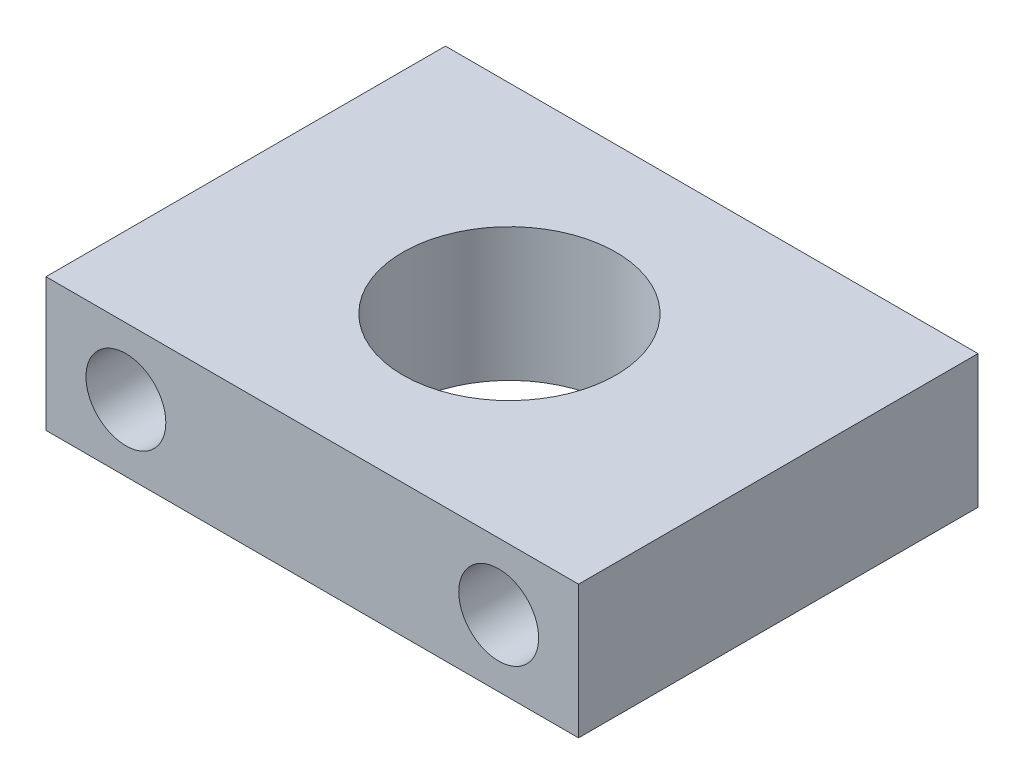
SolidWorks part; units mm, degrees
ref_plane "前视基准面" through (0, 0, 0) normal (0, 0, 1) x (1, 0, 0)
ref_plane "上视基准面" through (0, 0, 0) normal (0, 1, 0) x (1, 0, 0)
ref_plane "右视基准面" through (0, 0, 0) normal (1, 0, 0) x (0, 0, -1)
sketch "Sketch1" plane through (0, 0, 0) normal (0, 1, 0) x (1, 0, 0)
  line L1 (-16.9831, 2.6773) -> (3.0169, 2.6773)
  line L2 (-16.9831, 2.6773) -> (-16.9831, -12.3227)
  line L3 (-16.9831, -12.3227) -> (3.0169, -12.3227)
  line L4 (3.0169, 2.6773) -> (3.0169, -12.3227)
  dimension "D1" = 20
  dimension "D2" = 15
extrude "Boss-Extrude1" add sketch "Sketch1" along normal blind 5
sketch "Sketch2" plane through (0, 0, 12.3227) normal (0, 0, 1) x (1, 0, 0)
  line L0 (-6.9831, 5) -> (-6.9831, 0) construction
  line L3 (-16.9831, 2.5) -> (9.1299, 2.5) construction
  circle A0 centre (-13.9831, 2.5) radius 1.5
  circle A1 centre (0.0169, 2.5) radius 1.5
  dimension "D1" = 14
extrude "Cut-Extrude1" cut sketch "Sketch2" against normal through all
sketch "Sketch3" plane through (0, 5, 0) normal (0, 1, 0) x (1, 0, 0)
  line L0 (-7.0803, 2.6773) -> (-7.0803, 6.5066) construction
  line L2 (-16.9831, -4.8227) -> (-13.1125, -4.8227) construction
  circle A0 centre (-7.0803, -4.8227) radius 4
extrude "Cut-Extrude2" cut sketch "Sketch3" against normal blind 5
